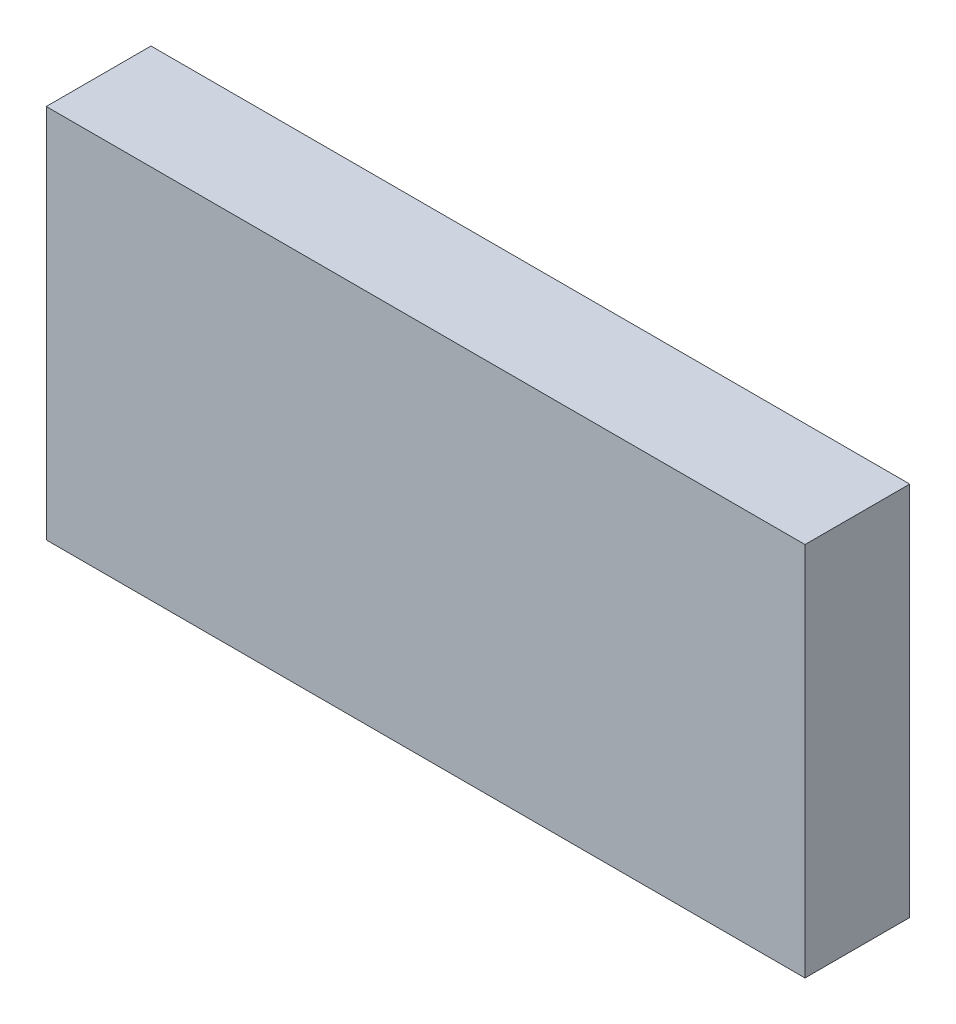
SolidWorks part; units mm, degrees
ref_plane "Front Plane" through (0, 0, 0) normal (0, 0, 1) x (1, 0, 0)
ref_plane "Top Plane" through (0, 0, 0) normal (0, 1, 0) x (1, 0, 0)
ref_plane "Right Plane" through (0, 0, 0) normal (1, 0, 0) x (0, 0, -1)
sketch "Sketch1" plane through (0, 0, 0) normal (0, 0, 1) x (1, 0, 0)
  line L0 (-0.1, -0.0746) -> (18.3, -0.0746)
  line L1 (18.3, -0.0746) -> (18.3, 9.0286)
  line L2 (18.3, 9.0286) -> (-0.1, 9.0286)
  line L3 (-0.1, 9.0286) -> (-0.1, -0.0746)
extrude "Component_Outline" add sketch "Sketch1" along normal blind 2.54 separate body
sketch3d "3DSketch1"
  line L0 (0, 0, 0) -> (1, 0, 0)
  line L1 (0, 0, 0) -> (0, 1, 0)
  line L2 (0, 0, 0) -> (0, 0, 1)
  point P0 (0, 0, 0)
